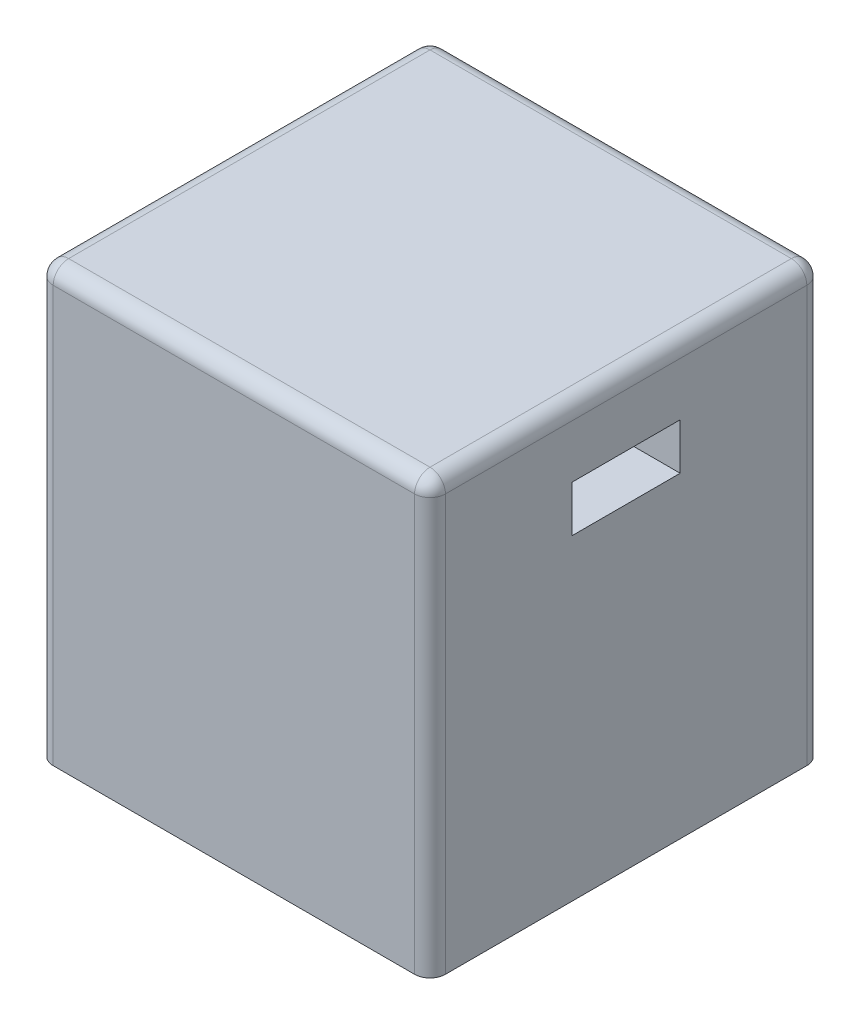
SolidWorks part; units mm, degrees
material "PLA"
ref_plane "Front Plane" through (0, 0, 0) normal (0, 0, 1) x (1, 0, 0)
ref_plane "Top Plane" through (0, 0, 0) normal (0, 1, 0) x (1, 0, 0)
ref_plane "Right Plane" through (0, 0, 0) normal (1, 0, 0) x (0, 0, -1)
sketch "Sketch1" plane through (0, 0, 0) normal (0, 1, 0) x (1, 0, 0)
  line L1 (-12.7, -12.7) -> (12.7, -12.7)
  line L2 (-12.7, -12.7) -> (-12.7, 12.7)
  line L3 (-12.7, 12.7) -> (12.7, 12.7)
  line L4 (12.7, -12.7) -> (12.7, 12.7)
  line L5 (-12.7, -12.7) -> (12.7, 12.7) construction
  line L6 (-12.7, 12.7) -> (12.7, -12.7) construction
  point P0 (0, 0)
  dimension "D1" = 25.4
  dimension "D2" = 25.4
extrude "Boss-Extrude1" add sketch "Sketch1" along normal mid plane 27.94
sketch "Sketch2" plane through (0, -13.97, 0) normal (0, -1, 0) x (1, 0, 0)
  line L0 (0, -6.35) -> (-12.7, -6.35) construction
  line L1 (-6.35, -6.35) -> (6.35, -6.35) construction
  line L2 (-6.35, -6.35) -> (-6.35, 6.35) construction
  line L3 (-6.35, 6.35) -> (6.35, 6.35) construction
  line L4 (6.35, -6.35) -> (6.35, 6.35) construction
  line L5 (-6.35, -6.35) -> (6.35, 6.35) construction
  line L6 (-6.35, 6.35) -> (6.35, -6.35) construction
  line L7 (-12.7, -12.7) -> (-12.7, 12.7) construction
  line L8 (6.35, 0) -> (6.35, 12.7) construction
  line L9 (-12.7, 12.7) -> (12.7, 12.7) construction
  circle A0 centre (-6.35, 6.35) radius 1.5
  circle A1 centre (6.35, 6.35) radius 1.5
  circle A2 centre (6.35, -6.35) radius 1.5
  circle A3 centre (-6.35, -6.35) radius 1.5
  point P0 (0, 0)
  dimension "D1" = 3
extrude "Cut-Extrude1" cut sketch "Sketch2" against normal blind 5.08
sketch "Sketch3" plane through (12.7, 0, 0) normal (1, 0, 0) x (0, 0, -1)
  line L1 (-3.5, 6.53) -> (3.5, 6.53)
  line L2 (-3.5, 6.53) -> (-3.5, 9.53)
  line L3 (-3.5, 9.53) -> (3.5, 9.53)
  line L4 (3.5, 6.53) -> (3.5, 9.53)
  line L5 (-3.5, 6.53) -> (3.5, 9.53) construction
  line L6 (-3.5, 9.53) -> (3.5, 6.53) construction
  line L7 (-12.7, -13.97) -> (12.7, -13.97) construction
  point P0 (0, 8.03)
  point P5 (0, 0)
  dimension "D1" = 7
  dimension "D2" = 3
  dimension "D3" = 22
extrude "Cut-Extrude2" cut sketch "Sketch3" against normal through all
fillet "Fillet1" radius 1 8 edges at (12.7, 0, -12.7) (-12.7, 0, -12.7) (12.7, 0, 12.7) (-12.7, 0, 12.7) (12.7, 13.97, 0) (0, 13.97, -12.7) (0, 13.97, 12.7) (-12.7, 13.97, 0)
ref_plane "Plane1" through (0, 8.03, 0) normal (0, 1, 0) x (1, 0, 0)
